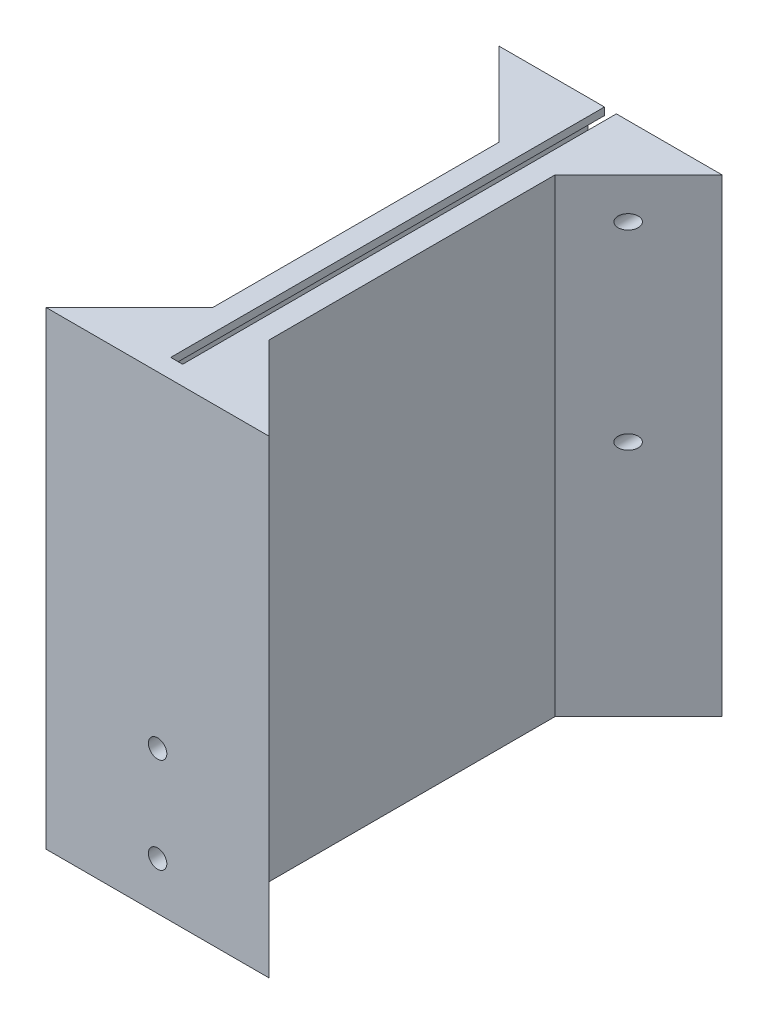
SolidWorks part; units mm, degrees
ref_plane "Front Plane" through (0, 0, 0) normal (0, 0, 1) x (1, 0, 0)
ref_plane "Top Plane" through (0, 0, 0) normal (0, 1, 0) x (1, 0, 0)
ref_plane "Right Plane" through (0, 0, 0) normal (1, 0, 0) x (0, 0, -1)
sketch "Sketch1" plane through (0, 0, 0) normal (0, 1, 0) x (1, 0, 0)
  line L0 (-29.725, -60.325) -> (29.725, -60.325)
  line L1 (29.725, -60.325) -> (7.5, -38.1)
  line L2 (7.5, -38.1) -> (7.5, 38.1)
  line L3 (7.5, 38.1) -> (29.725, 60.325)
  line L4 (29.725, 60.325) -> (-29.725, 60.325)
  line L5 (-29.725, 60.325) -> (-7.5, 38.1)
  line L6 (-7.5, 38.1) -> (-7.5, -38.1)
  line L7 (-7.5, -38.1) -> (-29.725, -60.325)
  dimension "D1" = 15
  dimension "D2" = 76.2
  dimension "D3" = 135
  dimension "D4" = 135
  dimension "D5" = 59.45
  dimension "D6" = 60.325
  dimension "D7" = 38.1
  dimension "D8" = 7.5
extrude "Boss-Extrude1" add sketch "Sketch1" along normal blind 125
sketch "Sketch3" plane through (0, 0, -60.325) normal (0, 0, -1) x (-1, 0, 0)
  line L0 (-6, 123) -> (-6, 55)
  line L1 (-6, 55) -> (6, 55)
  line L2 (6, 55) -> (6, 123)
  line L3 (6, 123) -> (-6, 123)
  line L4 (-29.725, 125) -> (29.725, 125) construction
  dimension "D1" = 68
  dimension "D2" = 12
  dimension "D3" = 6
  dimension "D4" = 2
extrude "Cut-Extrude1" cut sketch "Sketch3" against normal blind 115.57
sketch "Sketch4" plane through (0, 125, 0) normal (0, 1, 0) x (1, 0, 0)
  line L0 (-1.5875, 60.325) -> (-1.5875, -55.245)
  line L1 (29.725, 60.325) -> (-29.725, 60.325) construction
  line L2 (-1.5875, -55.245) -> (1.5875, -55.245)
  line L3 (1.5875, -55.245) -> (1.5875, 60.325)
  line L4 (1.5875, 60.325) -> (-1.5875, 60.325)
  dimension "D1" = 3.175
  dimension "D2" = 115.57
  dimension "D3" = 1.5875
extrude "Cut-Extrude2" cut sketch "Sketch4" against normal blind 3
sketch "Sketch5" plane through (0, 0, 0) normal (0, -1, 0) x (1, 0, 0)
  line L0 (4, -9.525) -> (4, 9.525)
  line L1 (4, 9.525) -> (-4, 9.525)
  line L2 (-4, -9.525) -> (4, -9.525)
  line L3 (-4, -9.525) -> (-4, 9.525)
  line L4 (7.5, 38.1) -> (7.5, -38.1) construction
  line L5 (29.725, -60.325) -> (-29.725, -60.325) construction
  dimension "D1" = 8
  dimension "D2" = 4
  dimension "D3" = 19.05
  dimension "D4" = 9.525
extrude "Cut-Extrude3" cut sketch "Sketch5" against normal up to next
sketch "Sketch6" plane through (0, 0, -60.325) normal (0, 0, -1) x (-1, 0, 0)
  line L0 (0, 55) -> (0, 0) construction
  line L1 (-6, 55) -> (6, 55) construction
  circle A0 centre (0, 12.7) radius 2.4575
  circle A1 centre (0, 38.1) radius 2.4575
  dimension "D1" = 4.9149
  dimension "D2" = 12.7
  dimension "D3" = 25.4
extrude "Cut-Extrude4" cut sketch "Sketch6" against normal blind 25.4
sketch "Sketch7" plane through (0, 0, 60.325) normal (0, 0, 1) x (1, 0, 0)
  line L0 (0, 125) -> (0, 0) construction
  line L1 (-29.725, 125) -> (29.725, 125) construction
  circle A0 centre (0, 38.1) radius 2.4575
  circle A1 centre (0, 12.7) radius 2.4574
  dimension "D1" = 4.9149
  dimension "D2" = 12.7
  dimension "D3" = 25.4
extrude "Cut-Extrude5" cut sketch "Sketch7" against normal blind 25.4
hole_wizard "Tap Drill for #10-24 Tap1" positions "Sketch9" profile "Sketch10" hole size "#10-24" standard "ANSI Inch"
sketch "Sketch9" plane through (0, 0, -60.325) normal (0, 0, -1) x (-1, 0, 0)
  line L0 (-29.725, 125) -> (-1.5875, 125) construction
  line L1 (-29.725, 125) -> (-29.725, 0) construction
  line L2 (29.725, 125) -> (29.725, 0) construction
  line L3 (1.5875, 125) -> (29.725, 125) construction
  point P0 (-17.225, 114.15)
  point P12 (-17.225, 63.35)
  point P15 (17.225, 114.15)
  point P20 (17.225, 63.35)
  dimension "D1" = 10.85
  dimension "D2" = 12.5
  dimension "D3" = 50.8
  dimension "D4" = 12.5
  dimension "D5" = 10.85
  dimension "D6" = 50.8
  dimension "D7" = 12.5
  dimension "D8" = 12.5
sketch "Sketch10" plane through (17.225, 114.15, -60.325) normal (1, 0, 0) x (0, 1, 0)
  line L0 (0, 0) -> (0, 31.1408)
  line L1 (0, 31.1408) -> (1.8986, 30)
  line L2 (1.8986, 30) -> (1.8986, 0)
  line L5 (1.8986, 0) -> (0, 0)
  line L10 (0, 31.1408) -> (-1.8987, 30) construction
  line L11 (0, -6.35) -> (0, 107.95) construction
  dimension "Hole Dia." = 3.7973
  dimension "Hole Depth" = 30
  dimension "Drill Angle" = 118
